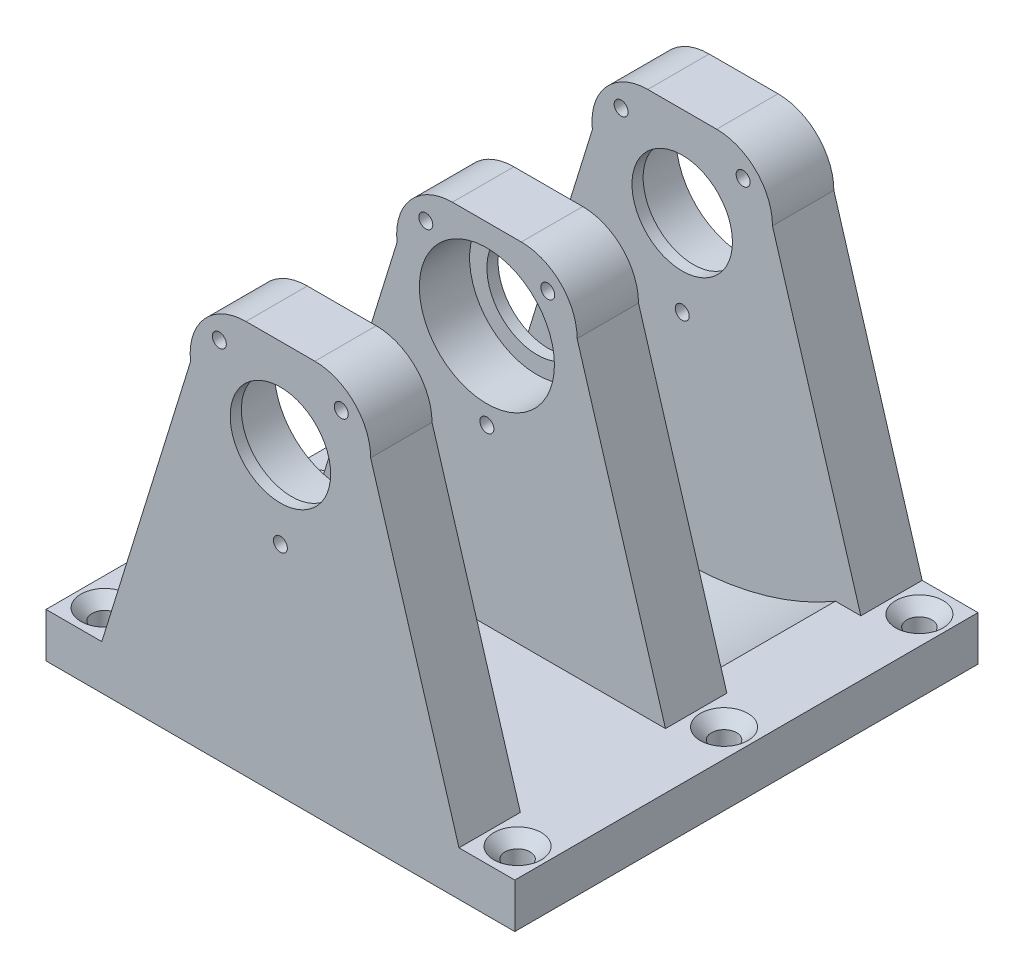
SolidWorks part; units mm, degrees
material "PET"
ref_plane "Piano frontale" through (0, 0, 0) normal (0, 0, 1) x (1, 0, 0)
ref_plane "Piano superiore" through (0, 0, 0) normal (0, 1, 0) x (1, 0, 0)
ref_plane "Piano destro" through (0, 0, 0) normal (1, 0, 0) x (0, 0, -1)
sketch "Schizzo1" plane through (0, 0, 0) normal (0, 0, 1) x (1, 0, 0)
  line L0 (-16.1, 0) -> (0, 0) construction
  line L1 (-6.1713, 16.1) -> (6.1713, 16.1)
  line L3 (-17, -54.5) -> (17, -54.5)
  line L5 (0, 0) -> (16.1, 0) construction
  line L7 (-17, -54.5) -> (-42, -54.5)
  line L11 (17, -54.5) -> (42, -54.5)
  line L16 (42, -54.5) -> (42, -46.5)
  line L18 (-42, -54.5) -> (-42, -46.5)
  line L20 (42, -46.5) -> (32, -46.5)
  line L21 (32, -46.5) -> (16.1713, 6.1)
  line L22 (-42, -46.5) -> (-32, -46.5)
  line L23 (-32, -46.5) -> (-16.1, 4.9079)
  circle A0 centre (0, 0) radius 12.1
  arc A1 (16.1713, 6.1) -> (6.1713, 16.1) centre (6.1713, 6.1) ccw
  arc A2 (-16.1, 4.9079) -> (-6.1713, 16.1) centre (-6.1713, 6.1) cw
  point P13 (0, -54.5)
  point P14 (0, 16.1)
  dimension "D1" = 24.2
  dimension "D3" = 25
  dimension "D4" = 10
  dimension "D7" = 8
  dimension "D2" = 16.1
  dimension "D5" = 54.5
  dimension "D6" = 34
  dimension "D8" = 10
  dimension "D9" = 10
extrude "Estrusione-Estrusione1" add sketch "Schizzo1" along normal blind 11
sketch "Schizzo2" plane through (0, 0, 11) normal (0, 0, 1) x (1, 0, 0)
  circle A0 centre (0, 0) radius 9
  circle A1 centre (0, 0) radius 12.1
  dimension "D1" = 18
extrude "Estrusione-Estrusione2" add sketch "Schizzo2" against normal blind 2
sketch "Schizzo3" plane through (0, -46.5, 0) normal (0, 1, 0) x (1, 0, 0)
  line L0 (32, -11) -> (42, 0) construction
  line L1 (-42, -11) -> (-32, 0) construction
  circle A0 centre (37, -5.5) radius 2.25
  circle A1 centre (-37, -5.5) radius 2.25
  dimension "D1" = 4.5
extrude "Taglio-Estrusione1" cut sketch "Schizzo3" against normal through all
chamfer "Smusso1" distance 2 angle 45 2 edges at (-37, -46.5, 7.75) (37, -46.5, 7.75)
sketch "Schizzo4" plane through (0, 0, 0) normal (0, 0, -1) x (-1, 0, 0)
  line L0 (-8.5791, 8.5329) -> (-13.2424, 13.1711) construction
  line L1 (8.6056, 8.5061) -> (13.2834, 13.1299) construction
  line L2 (0, -12.1) -> (0, -18.6772) construction
  arc A0 (-6.1713, 16.1) -> (-16.1713, 6.1) centre (-6.1713, 6.1) ccw construction
  arc A1 (16.1, 4.9079) -> (6.1713, 16.1) centre (6.1713, 6.1) ccw construction
  circle A2 centre (0, 0) radius 12.1 construction
  circle A3 centre (0, 0) radius 12.1 construction
  circle A4 centre (-10.9107, 10.852) radius 1.25
  circle A5 centre (10.9445, 10.818) radius 1.25
  circle A6 centre (0, -15.3886) radius 1.25
  dimension "D1" = 2.5
extrude "Taglio-Estrusione2" cut sketch "Schizzo4" against normal through all
sketch "Schizzo5" plane through (0, 0, 11) normal (0, 0, 1) x (1, 0, 0)
  line L1 (-42, -46.5) -> (42, -46.5)
  line L2 (-42, -46.5) -> (-42, -54.5)
  line L3 (-42, -54.5) -> (42, -54.5)
  line L4 (42, -46.5) -> (42, -54.5)
  circle A0 centre (0, 0) radius 54
  line M4 (-42, -54.5) -> (42, -54.5)
  line M5 (42, -54.5) -> (42, -46.5)
  line M6 (42, -46.5) -> (32, -46.5)
  line M12 (-32, -46.5) -> (-42, -46.5)
  line M13 (-42, -46.5) -> (-42, -54.5)
  dimension "D1" = 108
extrude "Estrusione-Estrusione4" add sketch "Schizzo5" along normal blind 24 contours A0 L1 M12 M13 M4 M5 M6
sketch "Schizzo7" plane through (0, 0, 35) normal (0, 0, 1) x (1, 0, 0)
  line L8 (42, -54.5) -> (42, -46.5)
  line L9 (-42, -54.5) -> (42, -54.5)
  line L10 (-42, -46.5) -> (-42, -54.5)
  line L11 (-32, -46.5) -> (-42, -46.5)
  line L12 (-16.1, 4.9079) -> (-32, -46.5)
  line L13 (6.1713, 16.1) -> (-6.1713, 16.1)
  line L14 (32, -46.5) -> (16.1713, 6.1)
  line L15 (42, -46.5) -> (32, -46.5)
  line L16 (42, -54.5) -> (42, -46.5)
  line L17 (-42, -54.5) -> (42, -54.5)
  line L18 (-42, -46.5) -> (-42, -54.5)
  line L19 (-32, -46.5) -> (-42, -46.5)
  line L20 (-16.1, 4.9079) -> (-32, -46.5)
  line L21 (6.1713, 16.1) -> (-6.1713, 16.1)
  line L22 (32, -46.5) -> (16.1713, 6.1)
  line L23 (42, -46.5) -> (32, -46.5)
  circle A0 centre (10.9107, 10.852) radius 1.25 construction
  circle A1 centre (10.9107, 10.852) radius 1.25
  arc A2 (-6.1713, 16.1) -> (-16.1, 4.9079) centre (-6.1713, 6.1) ccw
  arc A3 (16.1713, 6.1) -> (6.1713, 16.1) centre (6.1713, 6.1) ccw
  arc A4 (-6.1713, 16.1) -> (-16.1, 4.9079) centre (-6.1713, 6.1) ccw
  arc A5 (16.1713, 6.1) -> (6.1713, 16.1) centre (6.1713, 6.1) ccw
  circle A6 centre (0, 0) radius 9 construction
  circle A7 centre (0, -15.3886) radius 1.25 construction
  circle A8 centre (-10.9445, 10.818) radius 1.25 construction
  circle A9 centre (0, 0) radius 9
  circle A10 centre (0, -15.3886) radius 1.25
  circle A11 centre (-10.9445, 10.818) radius 1.25
  dimension "D1" = 0
extrude "Estrusione-Estrusione5" add sketch "Schizzo7" along normal blind 2
sketch "Schizzo8" plane through (0, 0, 37) normal (0, 0, 1) x (1, 0, 0)
  line L8 (42, -46.5) -> (32, -46.5)
  line L9 (32, -46.5) -> (16.1713, 6.1)
  line L10 (6.1713, 16.1) -> (-6.1713, 16.1)
  line L11 (-16.1, 4.9079) -> (-32, -46.5)
  line L12 (-32, -46.5) -> (-42, -46.5)
  line L13 (-42, -46.5) -> (-42, -54.5)
  line L14 (-42, -54.5) -> (42, -54.5)
  line L15 (42, -54.5) -> (42, -46.5)
  line L16 (42, -46.5) -> (32, -46.5)
  line L17 (32, -46.5) -> (16.1713, 6.1)
  line L18 (6.1713, 16.1) -> (-6.1713, 16.1)
  line L19 (-16.1, 4.9079) -> (-32, -46.5)
  line L20 (-32, -46.5) -> (-42, -46.5)
  line L21 (-42, -46.5) -> (-42, -54.5)
  line L22 (-42, -54.5) -> (42, -54.5)
  line L23 (42, -54.5) -> (42, -46.5)
  circle A0 centre (0, 0) radius 12.1 construction
  circle A1 centre (10.9107, 10.852) radius 1.25 construction
  arc A2 (16.1713, 6.1) -> (6.1713, 16.1) centre (6.1713, 6.1) ccw
  arc A3 (-6.1713, 16.1) -> (-16.1, 4.9079) centre (-6.1713, 6.1) ccw
  arc A4 (16.1713, 6.1) -> (6.1713, 16.1) centre (6.1713, 6.1) ccw
  arc A5 (-6.1713, 16.1) -> (-16.1, 4.9079) centre (-6.1713, 6.1) ccw
  circle A6 centre (0, -15.3886) radius 1.25 construction
  circle A7 centre (-10.9445, 10.818) radius 1.25 construction
  circle A8 centre (0, 0) radius 12.1
  circle A9 centre (10.9107, 10.852) radius 1.25
  circle A10 centre (0, -15.3886) radius 1.25
  circle A11 centre (-10.9445, 10.818) radius 1.25
  dimension "D1" = 0
extrude "Estrusione-Estrusione6" add sketch "Schizzo8" along normal blind 9
sketch "Schizzo10" plane through (0, 0, 46) normal (0, 0, 1) x (1, 0, 0)
  line L1 (-42, -46.5) -> (42, -46.5)
  line L2 (-42, -46.5) -> (-42, -54.5)
  line L3 (-42, -54.5) -> (42, -54.5)
  line L4 (42, -46.5) -> (42, -54.5)
extrude "Estrusione-Estrusione8" add sketch "Schizzo10" along normal blind 26
sketch "Schizzo11" plane through (0, 0, 72) normal (0, 0, 1) x (1, 0, 0)
  line L4 (-32, -46.5) -> (32, -46.5)
  line L5 (32, -46.5) -> (16.1713, 6.1)
  line L6 (6.1713, 16.1) -> (-6.1713, 16.1)
  line L7 (-16.1, 4.9079) -> (-32, -46.5)
  line L8 (-32, -46.5) -> (32, -46.5)
  line L9 (32, -46.5) -> (16.1713, 6.1)
  line L10 (6.1713, 16.1) -> (-6.1713, 16.1)
  line L11 (-16.1, 4.9079) -> (-32, -46.5)
  line L12 (-42, -46.5) -> (-42, -54.5)
  line L13 (-42, -54.5) -> (42, -54.5)
  line L14 (42, -54.5) -> (42, -46.5)
  line L15 (42, -46.5) -> (-42, -46.5)
  line L16 (-42, -46.5) -> (-42, -54.5)
  line L17 (-42, -54.5) -> (42, -54.5)
  line L18 (42, -54.5) -> (42, -46.5)
  line L19 (42, -46.5) -> (-42, -46.5)
  circle A0 centre (0, -15.3886) radius 1.25 construction
  circle A1 centre (10.9107, 10.852) radius 1.25 construction
  arc A2 (16.1713, 6.1) -> (6.1713, 16.1) centre (6.1713, 6.1) ccw
  arc A3 (-6.1713, 16.1) -> (-16.1, 4.9079) centre (-6.1713, 6.1) ccw
  arc A4 (16.1713, 6.1) -> (6.1713, 16.1) centre (6.1713, 6.1) ccw
  arc A5 (-6.1713, 16.1) -> (-16.1, 4.9079) centre (-6.1713, 6.1) ccw
  circle A6 centre (-10.9445, 10.818) radius 1.25 construction
  circle A7 centre (0, 0) radius 12.1 construction
  circle A8 centre (0, -15.3886) radius 1.25
  circle A9 centre (10.9107, 10.852) radius 1.25
  circle A10 centre (-10.9445, 10.818) radius 1.25
  circle A11 centre (0, 0) radius 12.1
  line M11 (-42, -46.5) -> (-42, -54.5)
  line M12 (-42, -54.5) -> (42, -54.5)
  line M13 (42, -54.5) -> (42, -46.5)
  line M14 (42, -46.5) -> (-42, -46.5)
  dimension "D1" = 0
  dimension "D2" = 0
extrude "Estrusione-Estrusione9" add sketch "Schizzo11" along normal blind 9 contours M14 M11 M12 M13 | L10 A5 L11 L9 A4 A11 A10 A9 A8 M14
sketch "Schizzo12" plane through (0, 0, 81) normal (0, 0, 1) x (1, 0, 0)
  line L8 (42, -46.5) -> (32, -46.5)
  line L9 (32, -46.5) -> (16.1713, 6.1)
  line L10 (6.1713, 16.1) -> (-6.1713, 16.1)
  line L11 (-16.1, 4.9079) -> (-32, -46.5)
  line L12 (-32, -46.5) -> (-42, -46.5)
  line L13 (-42, -46.5) -> (-42, -54.5)
  line L14 (-42, -54.5) -> (42, -54.5)
  line L15 (42, -54.5) -> (42, -46.5)
  line L16 (42, -46.5) -> (32, -46.5)
  line L17 (32, -46.5) -> (16.1713, 6.1)
  line L18 (6.1713, 16.1) -> (-6.1713, 16.1)
  line L19 (-16.1, 4.9079) -> (-32, -46.5)
  line L20 (-32, -46.5) -> (-42, -46.5)
  line L21 (-42, -46.5) -> (-42, -54.5)
  line L22 (-42, -54.5) -> (42, -54.5)
  line L23 (42, -54.5) -> (42, -46.5)
  circle A0 centre (10.9107, 10.852) radius 1.25 construction
  circle A1 centre (-10.9445, 10.818) radius 1.25
  circle A2 centre (-10.9445, 10.818) radius 1.25
  circle A3 centre (0, -15.3886) radius 1.25
  circle A4 centre (0, -15.3886) radius 1.25
  circle A5 centre (0, 0) radius 9 construction
  circle A6 centre (10.9107, 10.852) radius 1.25
  circle A7 centre (0, 0) radius 9
  arc A10 (16.1713, 6.1) -> (6.1713, 16.1) centre (6.1713, 6.1) ccw
  arc A11 (-6.1713, 16.1) -> (-16.1, 4.9079) centre (-6.1713, 6.1) ccw
  arc A12 (16.1713, 6.1) -> (6.1713, 16.1) centre (6.1713, 6.1) ccw
  arc A13 (-6.1713, 16.1) -> (-16.1, 4.9079) centre (-6.1713, 6.1) ccw
  dimension "D1" = 0
  dimension "D2" = 0
  dimension "D3" = 0
extrude "Estrusione-Estrusione10" add sketch "Schizzo12" along normal blind 2
sketch "Schizzo13" plane through (0, -46.5, 0) normal (0, 1, 0) x (1, 0, 0)
  line L0 (32, -46) -> (42, -35)
  line L1 (42, -83) -> (42, 0) construction
  line L2 (32, -72) -> (42, -83)
  line L3 (-32, -35) -> (-42, -46)
  line L4 (-42, -83) -> (-42, 0) construction
  line L5 (-32, -72) -> (-42, -83)
  circle A0 centre (-37, -40.5) radius 2.25
  circle A1 centre (-37, -77.5) radius 2.25
  circle A2 centre (37, -40.5) radius 2.25
  circle A3 centre (37, -77.5) radius 2.25
  circle A4 centre (-37, -5.5) radius 2.25 construction
extrude "Taglio-Estrusione3" cut sketch "Schizzo13" against normal through all contours L0 A2 | L0 A2 | L3 A0 | L3 A0 | L5 A1 | L5 A1 | L2 A3 | L2 A3
chamfer "Smusso2" distance 2 angle 45 4 edges at (-37, -46.5, 42.75) (-37, -46.5, 79.75) (37, -46.5, 79.75) (37, -46.5, 42.75)
